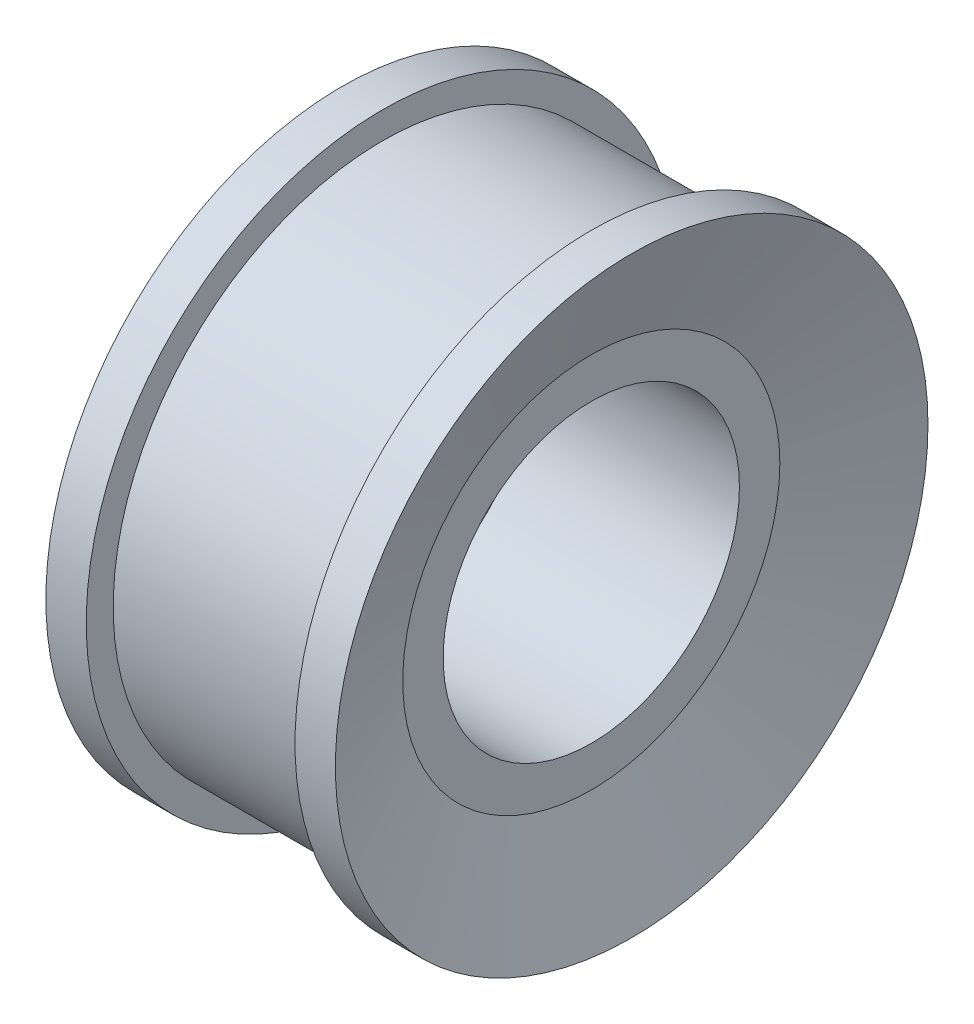
SolidWorks part; units mm, degrees
ref_plane "Front Plane" through (0, 0, 0) normal (0, 0, 1) x (1, 0, 0)
ref_plane "Top Plane" through (0, 0, 0) normal (0, 1, 0) x (1, 0, 0)
ref_plane "Right Plane" through (0, 0, 0) normal (1, 0, 0) x (0, 0, -1)
sketch "Sketch2" plane through (0, 0, 0) normal (0, 0, 1) x (1, 0, 0)
  line L0 (0, 0) -> (0, 24.9482) construction
  line L1 (-7.75, 11) -> (7.75, 11)
  line L3 (-7.75, 20) -> (7.75, 20)
  line L4 (7.75, 11) -> (7.75, 20)
  line L9 (-7.75, 11) -> (-7.75, 20)
  line L10 (7.75, 20) -> (7.75, 22)
  line L11 (7.75, 22) -> (10.75, 22)
  line L12 (7.75, 14) -> (10.75, 22)
  line L13 (-7.75, 14) -> (-10.75, 22)
  line L14 (-7.75, 22) -> (-10.75, 22)
  line L15 (-7.75, 20) -> (-7.75, 22)
  line L16 (-7.75, 11) -> (-7.75, 20)
  point P2 (0, 11)
  point P7 (0, 20)
  dimension "D1" = 15.5
  dimension "D2" = 11
  dimension "D3" = 20
  dimension "D4" = 2
  dimension "D5" = 3
  dimension "D6" = 3
ref_axis "Axis1" through (11.825, 0, 0) along (-1, 0, 0)
revolve "Revolve1" add sketch "Sketch2" angle 360 about axis through (11.825, 0, 0) along (-1, 0, 0)
